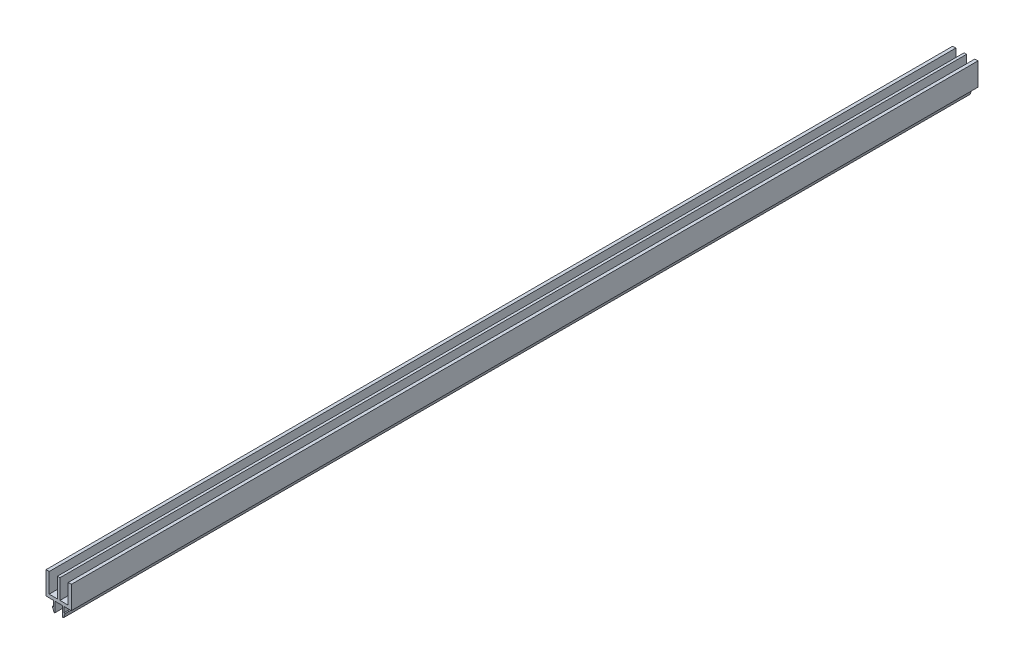
SolidWorks part; units mm, degrees
ref_plane "Plan de face" through (0, 0, 0) normal (0, 0, 1) x (1, 0, 0)
ref_plane "Plan de dessus" through (0, 0, 0) normal (0, 1, 0) x (1, 0, 0)
ref_plane "Plan de droite" through (0, 0, 0) normal (1, 0, 0) x (0, 0, -1)
ref_plane "Plan1" through (0, 0, 50) normal (0, 0, 1) x (1, 0, 0)
sketch "Esquisse1" plane through (0, 0, 50) normal (0, 0, 1) x (1, 0, 0)
  line L0 (-1, 2.5) -> (-7.5, 2.5)
  line L1 (-7.5, 2.5) -> (-7.5, 18)
  line L2 (-7.5, 18) -> (-10, 18)
  line L3 (-10, 18) -> (-10, 0)
  line L4 (-10, 0) -> (-4, 0)
  line L5 (-4, 0) -> (-4, -4.5)
  line L6 (-4, -4.5) -> (-5, -4.5)
  line L7 (-5, -4.5) -> (-3.75, -8)
  line L8 (-3.75, -8) -> (-3, -8)
  line L9 (-3, -8) -> (-3, 0)
  line L10 (-3, 0) -> (3, 0)
  line L11 (3, 0) -> (3, -8)
  line L12 (3, -8) -> (3.75, -8)
  line L13 (3.75, -8) -> (5, -4.5)
  line L14 (5, -4.5) -> (4, -4.5)
  line L15 (4, -4.5) -> (4, 0)
  line L16 (4, 0) -> (10, 0)
  line L17 (10, 0) -> (10, 18)
  line L18 (10, 18) -> (7.5, 18)
  line L19 (7.5, 18) -> (7.5, 2.5)
  line L20 (7.5, 2.5) -> (1, 2.5)
  line L21 (1, 2.5) -> (1, 18)
  line L22 (1, 18) -> (-1, 18)
  line L23 (-1, 18) -> (-1, 2.5)
extrude "Boss.-Extru.1" add sketch "Esquisse1" against normal blind 715
